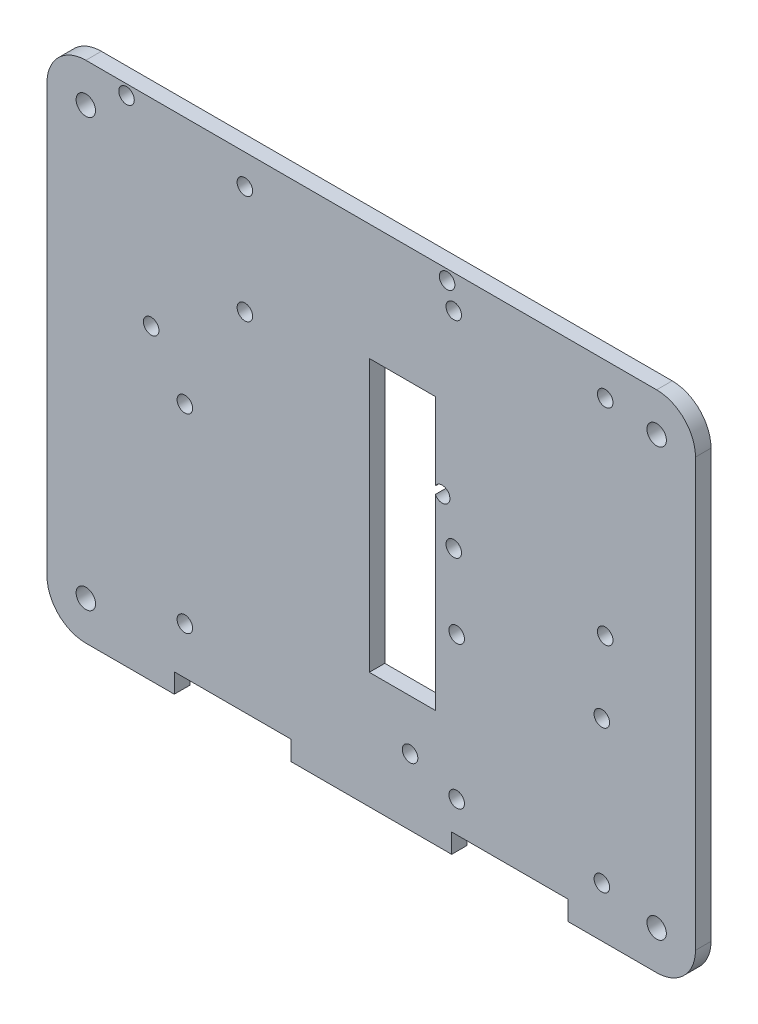
SolidWorks part; units mm, degrees
ref_plane "Front Plane" through (0, 0, 0) normal (0, 0, 1) x (1, 0, 0)
ref_plane "Top Plane" through (0, 0, 0) normal (0, 1, 0) x (1, 0, 0)
ref_plane "Right Plane" through (0, 0, 0) normal (1, 0, 0) x (0, 0, -1)
sketch "Sketch1" plane through (0, 0, 0) normal (0, 0, 1) x (1, 0, 0)
  line L1 (-83.5, 65) -> (83.5, 65)
  line L2 (-83.5, 65) -> (-83.5, -65)
  line L3 (-83.5, -65) -> (83.5, -65)
  line L4 (83.5, 65) -> (83.5, -65)
  line L5 (-83.5, 65) -> (83.5, -65) construction
  line L6 (-83.5, -65) -> (83.5, 65) construction
  point P0 (0, 0)
  dimension "D1" = 130
  dimension "D2" = 167
extrude "Boss-Extrude1" add sketch "Sketch1" along normal blind 4
fillet "Fillet1" radius 10 2 edges at (-83.5, -65, 2) (-83.5, 65, 2)
fillet "Fillet2" radius 10 2 edges at (83.5, -65, 2) (83.5, 65, 2)
sketch "Sketch4" plane through (0, 0, 4) normal (0, 0, 1) x (1, 0, 0)
  line L0 (73.5, 65) -> (-73.5, 65) construction
  line L1 (8.5, 35) -> (23.5, 35)
  line L2 (8.5, 35) -> (8.5, -15)
  line L3 (8.5, -15) -> (23.5, -15)
  line L4 (23.5, 35) -> (23.5, -15)
  line L5 (8.5, 35) -> (23.5, -15) construction
  line L6 (8.5, -15) -> (23.5, 35) construction
  line L7 (83.5, -55) -> (83.5, 55) construction
  point P0 (16, 10)
  dimension "D1" = 50
  dimension "D2" = 30
  dimension "D3" = 60
  dimension "D4" = 15
extrude "Cut-Extrude3" [suppressed] cut sketch "Sketch4" against normal blind 70
sketch "Sketch5" plane through (0, 0, 4) normal (0, 0, 1) x (1, 0, 0)
  circle A0 centre (-73.5, 55) radius 2.5
  circle A1 centre (73.5, 55) radius 2.5
  circle A2 centre (-73.5, -55) radius 2.5
  circle A3 centre (73.5, -55) radius 2.5
  dimension "D1" = 5
extrude "Cut-Extrude4" cut sketch "Sketch5" against normal blind 70
sketch "Sketch6" plane through (0, 0, 4) normal (0, 0, 1) x (1, 0, 0)
  line L0 (-73.5, -65) -> (73.5, -65) construction
  line L1 (-50.715, -65) -> (-20.715, -65)
  line L2 (-50.715, -65) -> (-50.715, -60)
  line L3 (-50.715, -60) -> (-20.715, -60)
  line L4 (-20.715, -65) -> (-20.715, -60)
  line L5 (-20.715, -65) -> (-20.715, -60) construction
  line L6 (-20.715, -60) -> (-50.715, -60) construction
  line L7 (0, 76.4763) -> (0, -17.1864) construction
  line L8 (50.715, -60) -> (20.715, -60)
  line L9 (50.715, -65) -> (50.715, -60)
  line L10 (50.715, -65) -> (20.715, -65)
  line L11 (20.715, -65) -> (20.715, -60)
  dimension "D1" = 5
extrude "Cut-Extrude5" cut sketch "Sketch6" against normal blind 10
sketch "Sketch7" plane through (0, 0, 4) normal (0, 0, 1) x (1, 0, 0)
  circle A0 centre (22.0068, -15.3143) radius 2
  circle A1 centre (59.3863, -15.3143) radius 2
  circle A2 centre (59.3863, -52.0561) radius 2
  circle A3 centre (22.0068, -52.0561) radius 2
  dimension "D1" = 4
extrude "Cut-Extrude6" cut sketch "Sketch7" against normal through all
sketch "Sketch8" plane through (0, 0, 4) normal (0, 0, 1) x (1, 0, 0)
  circle A0 centre (21.25, 56.5) radius 2
  circle A1 centre (60.25, 56.5) radius 2
  circle A2 centre (60.25, 3.5) radius 2
  circle A3 centre (21.25, 3.5) radius 2
  dimension "D1" = 4
extrude "Cut-Extrude7" cut sketch "Sketch8" against normal through all
sketch "Sketch9" plane through (0, 0, 4) normal (0, 0, 1) x (1, 0, 0)
  line L0 (83.5, -55) -> (83.5, 55) construction
  line L1 (-0.5, 35) -> (16.5, 35)
  line L2 (-0.5, 35) -> (-0.5, -35)
  line L3 (-0.5, -35) -> (16.5, -35)
  line L4 (16.5, 35) -> (16.5, -35)
  line L5 (-0.5, 35) -> (16.5, -35) construction
  line L6 (-0.5, -35) -> (16.5, 35) construction
  point P0 (8, 0)
  point P7 (83.5, 0)
  dimension "D1" = 17
  dimension "D2" = 70
  dimension "D3" = 67
extrude "Cut-Extrude8" cut sketch "Sketch9" against normal through all
sketch "Sketch10" plane through (0, 0, 4) normal (0, 0, 1) x (1, 0, 0)
  circle A0 centre (-48, 1.0821) radius 2
  circle A1 centre (10, -47.9179) radius 2
  circle A2 centre (-48, -47.9179) radius 2
  circle A3 centre (10, 1.0821) radius 2
  dimension "D1" = 4
extrude "Cut-Extrude9" cut sketch "Sketch10" against normal through all
sketch "Sketch11" plane through (0, 0, 4) normal (0, 0, 1) x (1, 0, 0)
  circle A0 centre (-63.02, 62.3785) radius 2
  circle A2 centre (-32.54, 57.2985) radius 2
  circle A4 centre (-32.54, 29.3585) radius 2
  circle A5 centre (19.53, 62.3785) radius 2
  circle A6 centre (18.26, 14.1185) radius 2
  circle A7 centre (-56.67, 14.1185) radius 2
  dimension "D1" = 4
extrude "Cut-Extrude10" cut sketch "Sketch11" against normal through all
